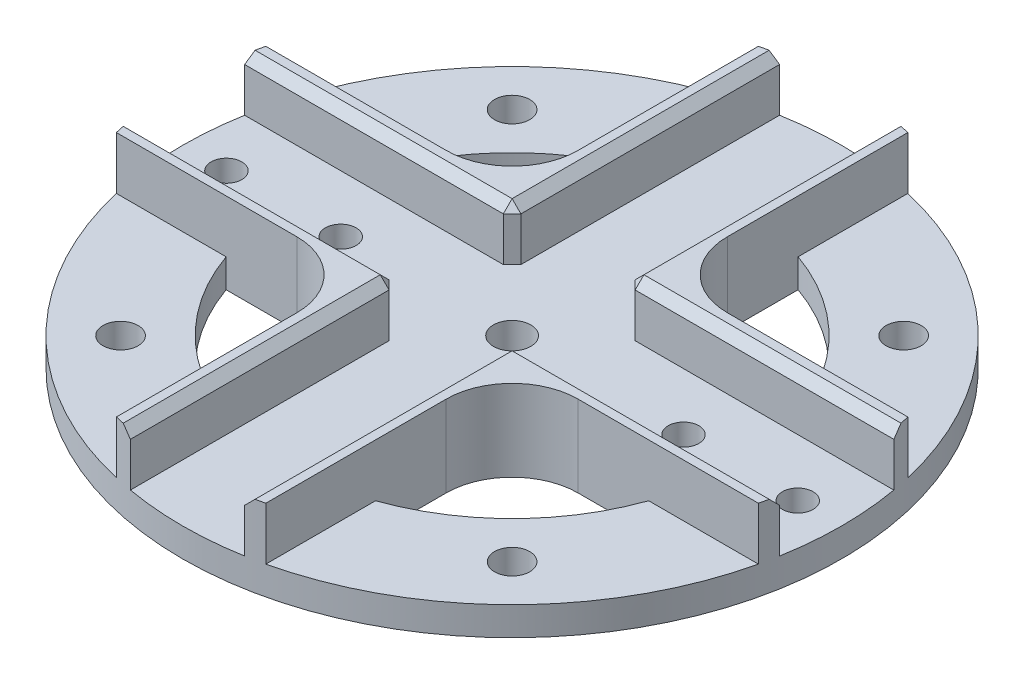
SolidWorks part; units mm, degrees
ref_plane "Front Plane" through (0, 0, 0) normal (0, 0, 1) x (1, 0, 0)
ref_plane "Top Plane" through (0, 0, 0) normal (0, 1, 0) x (1, 0, 0)
ref_plane "Right Plane" through (0, 0, 0) normal (1, 0, 0) x (0, 0, -1)
sketch "Sketch1" plane through (0, 0, 0) normal (0, 1, 0) x (1, 0, 0)
  circle A0 centre (0, 0) radius 75
  circle A1 centre (0, 0) radius 4.25
  dimension "D1" = 150
  dimension "D2" = 8.5
extrude "Boss-Extrude1" add sketch "Sketch1" along normal blind 6.5
sketch "Sketch2" plane through (0, 6.5, 0) normal (0, 1, 0) x (1, 0, 0)
  line L32 (-13, -13) -> (-73.8647, -13)
  line L33 (-13, -13) -> (-13, -73.8647)
  line L47 (-17, -32) -> (-17, -73.0479)
  line L48 (-32, -17) -> (-73.0479, -17)
  line L49 (0, 0) -> (-19.05, 0) construction
  line L50 (0, 0) -> (0, 16.1949) construction
  line L51 (-32, 17) -> (-73.0479, 17)
  line L52 (-13, 13) -> (-73.8647, 13)
  line L53 (-13, 13) -> (-13, 73.8647)
  line L54 (-17, 32) -> (-17, 73.0479)
  line L56 (17, 32) -> (17, 73.0479)
  line L57 (13, 13) -> (13, 73.8647)
  line L58 (13, 13) -> (73.8647, 13)
  line L59 (32, 17) -> (73.0479, 17)
  line L60 (32, -17) -> (73.0479, -17)
  line L61 (13, -13) -> (73.8647, -13)
  line L62 (13, -13) -> (13, -73.8647)
  line L63 (17, -32) -> (17, -73.0479)
  arc A5 (-17, -73.0479) -> (-13, -73.8647) centre (0, 0) ccw
  arc A6 (-73.8647, -13) -> (-73.0479, -17) centre (0, 0) ccw
  arc A7 (-73.8647, 13) -> (-73.0479, 17) centre (0, 0) cw
  arc A8 (-17, 73.0479) -> (-13, 73.8647) centre (0, 0) cw
  arc A9 (17, 73.0479) -> (13, 73.8647) centre (0, 0) ccw
  arc A10 (73.8647, 13) -> (73.0479, 17) centre (0, 0) ccw
  arc A11 (73.8647, -13) -> (73.0479, -17) centre (0, 0) cw
  arc A12 (17, -73.0479) -> (13, -73.8647) centre (0, 0) cw
  arc A13 (32, -17) -> (17, -32) centre (32, -32) ccw
  arc A14 (17, 32) -> (32, 17) centre (32, 32) ccw
  arc A15 (-32, 17) -> (-17, 32) centre (-32, 32) ccw
  arc A16 (-17, -32) -> (-32, -17) centre (-32, -32) ccw
  point P29 (17, -17)
  point P32 (17, 17)
  point P35 (-17, 17)
  point P38 (-17, -17)
  dimension "D5" = 15
  dimension "D1" = 13
  dimension "D2" = 13
  dimension "D3" = 4
  dimension "D4" = 4
extrude "Boss-Extrude2" add sketch "Sketch2" along normal blind 12
chamfer "Chamfer1" distance 2 angle 45 12 edges at (13, 12.5, -13) (43.4324, 18.5, -13) (13, 18.5, -43.4324) (-13, 12.5, -13) (-13, 18.5, -43.4324) (-43.4324, 18.5, -13) (-13, 12.5, 13) (-43.4324, 18.5, 13) (-13, 18.5, 43.4324) (13, 12.5, 13) (13, 18.5, 43.4324) (43.4324, 18.5, 13)
sketch "Sketch3" plane through (0, 6.5, 0) normal (0, 1, 0) x (1, 0, 0)
  line L4 (32, -17) -> (73.0479, -17) construction
  line L18 (32, -17) -> (48.0833, -17)
  line L20 (17, -32) -> (17, -48.0833)
  line L22 (0, 0) -> (0, -22.6064) construction
  line L23 (0, 0) -> (-26.2616, 0) construction
  line L24 (-17, -32) -> (-17, -48.0833)
  line L25 (-32, -17) -> (-48.0833, -17)
  line L26 (17, 32) -> (17, 48.0833)
  line L27 (32, 17) -> (48.0833, 17)
  line L28 (-32, 17) -> (-48.0833, 17)
  line L29 (-17, 32) -> (-17, 48.0833)
  arc A9 (17, -48.0833) -> (48.0833, -17) centre (0, 0) ccw
  arc A10 (32, -17) -> (17, -32) centre (32, -32) ccw
  arc A11 (-32, -17) -> (-17, -32) centre (-32, -32) cw
  arc A12 (-17, -48.0833) -> (-48.0833, -17) centre (0, 0) cw
  arc A13 (32, 17) -> (17, 32) centre (32, 32) cw
  arc A14 (17, 48.0833) -> (48.0833, 17) centre (0, 0) cw
  arc A15 (-17, 48.0833) -> (-48.0833, 17) centre (0, 0) ccw
  arc A16 (-32, 17) -> (-17, 32) centre (-32, 32) ccw
  dimension "D3" = 102
extrude "Cut-Extrude1" cut sketch "Sketch3" against normal up to surface (6.5 mm away) up to face at (0, 0, 75)
sketch "Sketch4" plane through (0, 6.5, 0) normal (0, 1, 0) x (1, 0, 0)
  line L0 (0, 0) -> (-44.5477, 44.5477) construction
  line L1 (0, 0) -> (-44.5477, -44.5477) construction
  line L2 (0, 0) -> (44.5477, -44.5477) construction
  line L3 (0, 0) -> (44.5477, 44.5477) construction
  circle A0 centre (0, 0) radius 63 construction
  circle A1 centre (44.5477, -44.5477) radius 4
  circle A2 centre (-44.5477, -44.5477) radius 4
  circle A3 centre (44.5477, 44.5477) radius 4
  circle A4 centre (-44.5477, 44.5477) radius 4
  dimension "D1" = 126
  dimension "D2" = 8
  dimension "D3" = 8
  dimension "D4" = 8
  dimension "D5" = 8
sketch "Sketch5" plane through (0, 6.5, 0) normal (0, 1, 0) x (1, 0, 0)
  line L0 (75, 0) -> (-75, 0) construction
  line L1 (0, 0) -> (0, 37.4363) construction
  circle A0 centre (65, 0) radius 3.5
  circle A1 centre (0, 0) radius 75 construction
  circle A2 centre (39, 0) radius 3.5
  circle A3 centre (-39, 0) radius 3.5
  circle A4 centre (-65, 0) radius 3.5
  dimension "D1" = 7
  dimension "D2" = 150
  dimension "D5" = 7
  dimension "D3" = 10
  dimension "D4" = 26
extrude "Cut-Extrude3" cut sketch "Sketch5" against normal up to surface (6.5 mm away) up to face at (-28.6244, 0, 28.6244)
extrude "Cut-Extrude5" cut sketch "Sketch4" against normal up to surface (6.5 mm away) up to face at (65, 0, 3.5)
